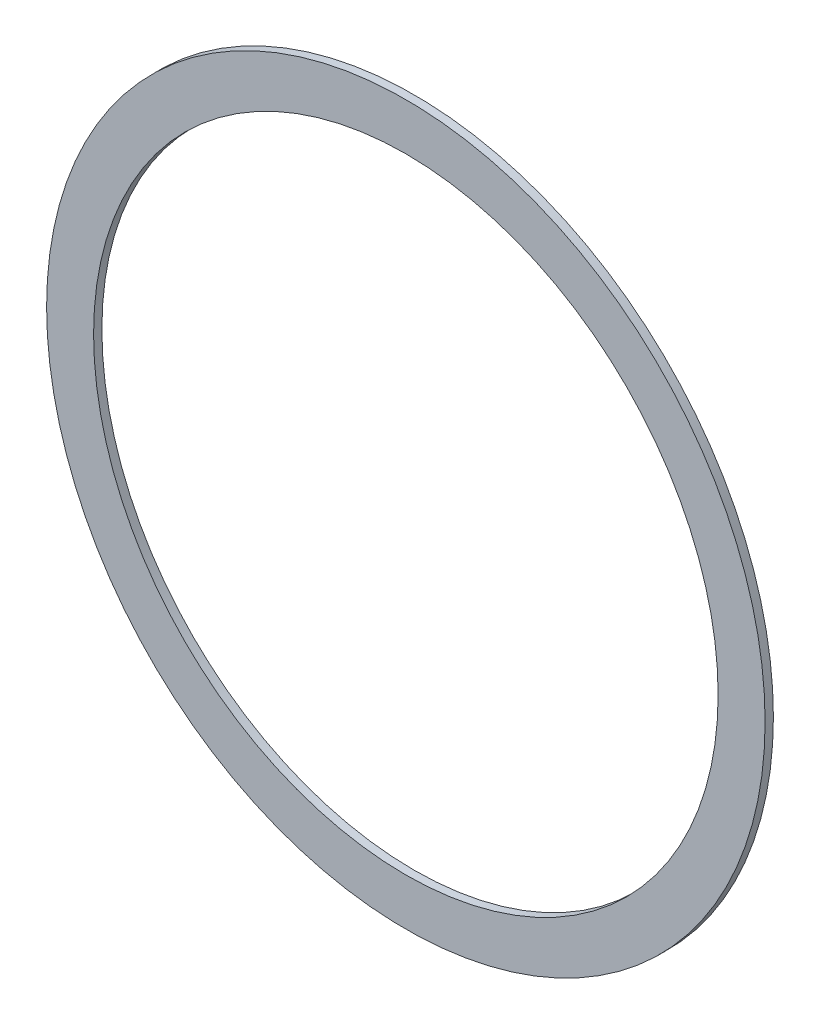
SolidWorks part; units mm, degrees
ref_plane "Front Plane" through (0, 0, 0) normal (0, 0, 1) x (1, 0, 0)
ref_plane "Top Plane" through (0, 0, 0) normal (0, 1, 0) x (1, 0, 0)
ref_plane "Right Plane" through (0, 0, 0) normal (1, 0, 0) x (0, 0, -1)
sketch "草圖1" plane through (0, 0, 0) normal (0, 0, 1) x (1, 0, 0)
  circle A0 centre (0, 0) radius 65
  circle A1 centre (0, 0) radius 56.5
extrude "填料-伸長1" add sketch "草圖1" along normal blind 1.5 from offset 11.5
